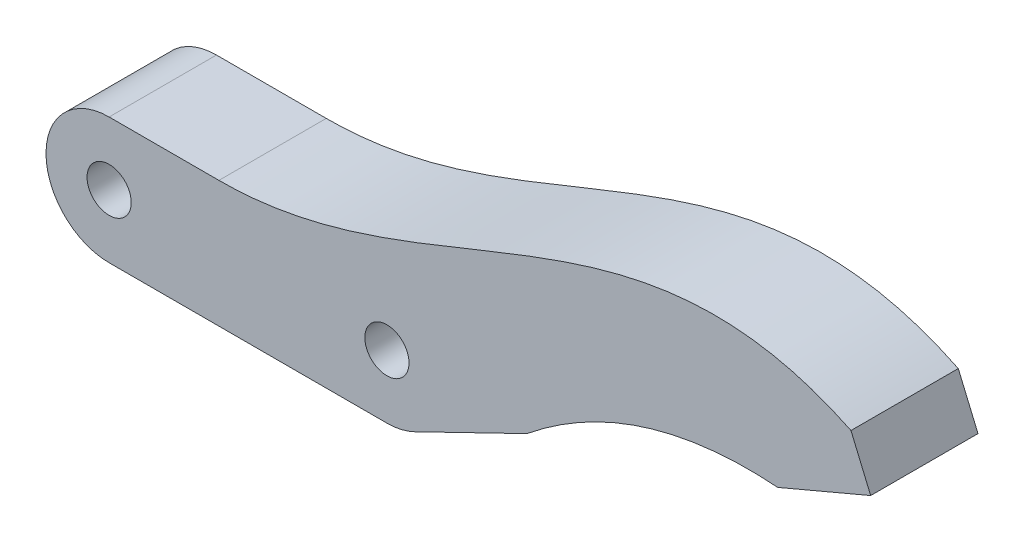
SolidWorks part; units mm, degrees
ref_plane "Front Plane" through (0, 0, 0) normal (0, 0, 1) x (1, 0, 0)
ref_plane "Top Plane" through (0, 0, 0) normal (0, 1, 0) x (1, 0, 0)
ref_plane "Right Plane" through (0, 0, 0) normal (1, 0, 0) x (0, 0, -1)
sketch "Sketch1" plane through (0, 0, 0) normal (0, 0, 1) x (1, 0, 0)
  line L1 (0, 0) -> (27, 0)
  line L2 (0, 0) -> (0, 10)
  line L3 (0, 10) -> (27, 10)
  circle A0 centre (5, 5) radius 5
  circle A1 centre (5, 5) radius 1.75
  circle A2 centre (27, 5) radius 5
  circle A3 centre (27, 5) radius 1.75
  dimension "D3" = 3.5
  dimension "D1" = 27
  dimension "D2" = 10
extrude "Boss-Extrude1" add sketch "Sketch1" along normal mid plane 8.5 contours A0 A1 | A2 L3 A0 L1 | A2 A3
sketch "Sketch2" plane through (0, 0, 4.25) normal (0, 0, 1) x (1, 0, 0)
  line L0 (5, 10) -> (27, 10) construction
  line L1 (5, 10) -> (13.695, 10) construction
  line L2 (29.1838, 0.5021) -> (38.0854, 4.8241)
  line L3 (57.948, 11.0678) -> (65.3138, 14.1895)
  line L4 (65.3138, 14.1895) -> (63.753, 17.8724)
  arc A0 (27, 0) -> (27, 10) centre (27, 5) ccw construction
  arc A1 (27, 0) -> (29.1838, 0.5021) centre (27, 5) ccw
  spline S0 degree 2 poles (38.0854, 4.8241) (46.7975, 11.8952) (57.948, 11.0678) knots 0 0 0 1 1 1
  spline S1 degree 3 poles (63.753, 17.8724) (45.9289, 26.5638) (31.0593, 10) (13.695, 10) knots 0 0 0 0 1 1 1 1
  arc M10 (27, 0) -> (27, 10) centre (27, 5) ccw
  line M11 (27, 10) -> (5, 10)
  dimension "D1" = 8
  dimension "D2" = 4
  dimension "D3" = 9.8953
extrude "Boss-Extrude2" add sketch "Sketch2" against normal blind 8.5 contours L4 S1 L2 S0 L3 M11 M10
